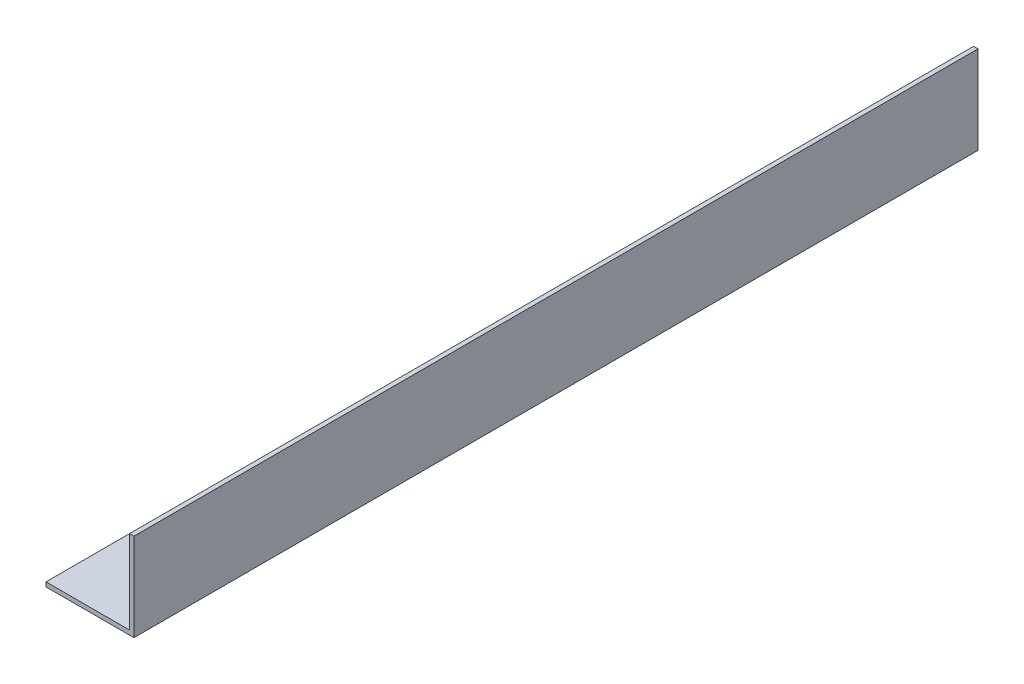
SolidWorks part; units mm, degrees
ref_plane "Front Plane" through (0, 0, 0) normal (0, 0, 1) x (1, 0, 0)
ref_plane "Top Plane" through (0, 0, 0) normal (0, 1, 0) x (1, 0, 0)
ref_plane "Right Plane" through (0, 0, 0) normal (1, 0, 0) x (0, 0, -1)
sketch "Sketch2" plane through (0, 0, 0) normal (0, 0, 1) x (1, 0, 0)
  line L0 (-15.875, 0) -> (15.875, 0)
  line L1 (15.875, 0) -> (15.875, 31.75)
  line L2 (15.875, 31.75) -> (14.2875, 31.75)
  line L3 (14.2875, 31.75) -> (14.2875, 1.9685)
  line L4 (13.9065, 1.5875) -> (-15.875, 1.5875)
  line L5 (-15.875, 0) -> (-15.875, 1.5875)
  line L6 (15.0813, 31.75) -> (15.875, 31.75) construction
  line L7 (-15.875, 0.7937) -> (-15.875, 0) construction
  arc A0 (13.9065, 1.5875) -> (14.2875, 1.9685) centre (13.9065, 1.9685) ccw
  dimension "Inner Radius" = 0.381
  dimension "Vert" = 31.75
  dimension "Horz" = 31.75
  dimension "Thickness" = 1.5875
extrude "Boss-Extrude1" add sketch "Sketch2" along normal mid plane 304.8
ref_plane "Contact Plane 1" through (0, 1.5875, 0) normal (0, 1, 0) x (1, 0, 0)
ref_plane "Contact Plane 2" through (14.2875, 0, 0) normal (-1, 0, 0) x (0, 0, 1)
